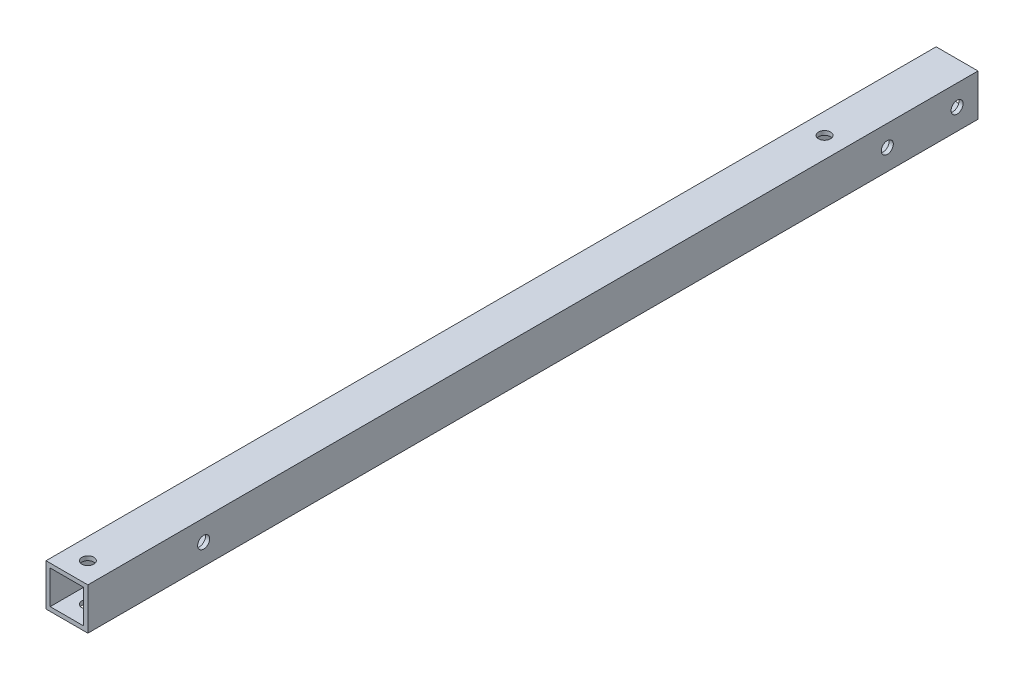
SolidWorks part; units mm, degrees
material "5052-H34"
ref_plane "正面" through (0, 0, 0) normal (0, 0, 1) x (1, 0, 0)
ref_plane "平面" through (0, 0, 0) normal (0, 1, 0) x (1, 0, 0)
ref_plane "右側面" through (0, 0, 0) normal (1, 0, 0) x (0, 0, -1)
sketch "ｽｹｯﾁ1" plane through (0, 0, 0) normal (0, 0, 1) x (1, 0, 0)
  line L1 (-7.5, 7.5) -> (7.5, 7.5)
  line L2 (-7.5, 7.5) -> (-7.5, -7.5)
  line L3 (-7.5, -7.5) -> (7.5, -7.5)
  line L4 (7.5, 7.5) -> (7.5, -7.5)
  line L5 (-7.5, 7.5) -> (7.5, -7.5) construction
  line L6 (-7.5, -7.5) -> (7.5, 7.5) construction
  point P0 (0, 0)
  dimension "D1" = 15
  dimension "D2" = 15
extrude "押し出し-薄板1" add sketch "ｽｹｯﾁ1" along normal blind 319 thin
sketch "ｽｹｯﾁ2" plane through (0, 7.5, 0) normal (0, 1, 0) x (1, 0, 0)
  line L0 (0, -319) -> (0, -47.5) construction
  line L1 (7.5, -319) -> (-7.5, -319) construction
  circle A0 centre (0, -47.5) radius 2.15
  circle A1 centre (0, -311.5) radius 2.15
  dimension "D3" = 4.3
  dimension "D1" = 264
  dimension "D2" = 7.5
extrude "ｶｯﾄ - 押し出し1" cut sketch "ｽｹｯﾁ2" against normal through all
sketch "ｽｹｯﾁ3" plane through (7.5, 0, 0) normal (1, 0, 0) x (0, 0, -1)
  line L0 (0, 0) -> (-32.5, 0) construction
  line L1 (-7.5, 0) -> (-277.5, 0) construction
  circle A0 centre (-32.5, 0) radius 2.15
  circle A1 centre (-7.5, 0) radius 2.15
  circle A2 centre (-277.5, 0) radius 2.15
  dimension "D1" = 4.3
  dimension "D5" = 4.3
  dimension "D2" = 25
  dimension "D3" = 7.5
  dimension "D4" = 270
extrude "ｶｯﾄ - 押し出し2" cut sketch "ｽｹｯﾁ3" against normal through all
